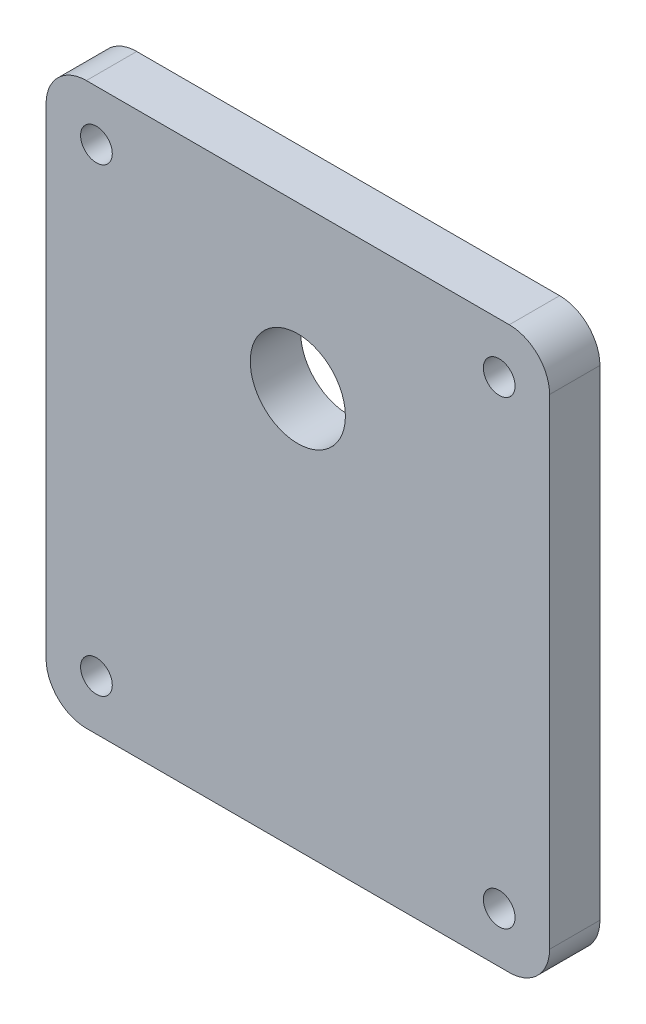
SolidWorks part; units mm, degrees
ref_plane "Front Plane" through (0, 0, 0) normal (0, 0, 1) x (1, 0, 0)
ref_plane "Top Plane" through (0, 0, 0) normal (0, 1, 0) x (1, 0, 0)
ref_plane "Right Plane" through (0, 0, 0) normal (1, 0, 0) x (0, 0, -1)
sketch "Sketch1" plane through (0, 0, 0) normal (0, 0, 1) x (1, 0, 0)
  line L0 (-19.6989, 23.2988) -> (-14.85, 29.7515)
  line L1 (-13.2512, 30.55) -> (13.2512, 30.55)
  line L2 (-20.1, 22.0973) -> (-20.1, -22.0973)
  line L3 (-13.2512, -30.55) -> (13.2512, -30.55)
  line L4 (20.1, 22.0973) -> (20.1, -22.0973)
  line L5 (-20.1, 30.55) -> (20.1, -30.55) construction
  line L6 (-20.1, -30.55) -> (20.1, 30.55) construction
  line L7 (14.85, 29.7515) -> (19.6989, 23.2988)
  line L8 (19.6989, -23.2988) -> (14.85, -29.7515)
  line L9 (-14.85, -29.7515) -> (-19.6989, -23.2988)
  arc A0 (-19.6989, -23.2988) -> (-20.1, -22.0973) centre (-18.1, -22.0973) cw
  arc A1 (-14.85, -29.7515) -> (-13.2512, -30.55) centre (-13.2512, -28.55) ccw
  arc A2 (14.85, -29.7515) -> (13.2512, -30.55) centre (13.2512, -28.55) cw
  arc A3 (19.6989, -23.2988) -> (20.1, -22.0973) centre (18.1, -22.0973) ccw
  arc A4 (19.6989, 23.2988) -> (20.1, 22.0973) centre (18.1, 22.0973) cw
  arc A5 (14.85, 29.7515) -> (13.2512, 30.55) centre (13.2512, 28.55) ccw
  arc A6 (-14.85, 29.7515) -> (-13.2512, 30.55) centre (-13.2512, 28.55) cw
  arc A7 (-19.6989, 23.2988) -> (-20.1, 22.0973) centre (-18.1, 22.0973) ccw
  point P0 (0, 0)
  point P16 (-20.1, -22.765)
  point P19 (-14.25, -30.55)
  point P22 (14.25, -30.55)
  point P25 (20.1, -22.765)
  point P28 (20.1, 22.765)
  point P31 (14.25, 30.55)
  point P34 (-14.25, 30.55)
  point P37 (-20.1, 22.765)
  dimension "D11" = 2
  dimension "D1" = 40.2
  dimension "D2" = 61.1
  dimension "D3" = 5.85
  dimension "D4" = 7.785
  dimension "D5" = 5.85
  dimension "D6" = 7.785
  dimension "D7" = 7.785
  dimension "D8" = 5.85
  dimension "D9" = 5.85
  dimension "D10" = 7.785
extrude "Boss-Extrude1" add sketch "Sketch1" against normal blind 6.35
sketch "Sketch2" plane through (0, 0, -6.35) normal (0, 0, -1) x (-1, 0, 0)
  line L0 (14.85, 29.7515) -> (14.85, -29.7515) construction
  line L1 (-14.85, 29.7515) -> (-14.85, -29.7515) construction
  line L2 (19.6989, 23.2988) -> (-19.6989, 23.2988) construction
  line L3 (20.1, -22.0973) -> (-20.1, -22.0973) construction
  line L4 (0, 30.55) -> (0, -30.55) construction
  line L5 (-13.2512, 30.55) -> (13.2512, 30.55) construction
  line L6 (13.2512, -30.55) -> (-13.2512, -30.55) construction
  circle A0 centre (17.3, 21.9488) radius 1.35
  circle A1 centre (17.3, -0.0512) radius 1.35
  circle A2 centre (17.3, -22.0512) radius 1.35
  circle A3 centre (11, -27.75) radius 1.385
  circle A4 centre (-11, -27.75) radius 1.385
  circle A5 centre (-17.3, -22.0512) radius 1.35
  circle A6 centre (-17.3, -0.0512) radius 1.35
  circle A7 centre (-17.3, 21.9488) radius 1.35
  dimension "D1" = 2.7
  dimension "D5" = 2.77
  dimension "D2" = 22
  dimension "D3" = 22
  dimension "D4" = 17.3
  dimension "D6" = 11
  dimension "D7" = 2.8
extrude "Cut-Extrude1" cut sketch "Sketch2" against normal through all
sketch "Sketch3" plane through (0, 0, -6.35) normal (0, 0, -1) x (-1, 0, 0)
  line L2 (-31.75, 38.2048) -> (31.75, 38.2048)
  line L3 (-31.75, 38.2048) -> (-31.75, -32.9152)
  line L4 (-31.75, -32.9152) -> (31.75, -32.9152)
  line L6 (31.75, 38.2048) -> (31.75, -32.9152)
  line L9 (-19.1605, 23.6188) -> (19.1605, 23.6188)
  line L10 (-19.1605, 23.6188) -> (-19.1605, -23.6188)
  line L11 (-19.1605, -23.6188) -> (19.1605, -23.6188)
  line L12 (19.1605, 23.6188) -> (19.1605, -23.6188)
  circle A0 centre (17.3, 21.9488) radius 1.35 construction
  point P0 (0, 0)
  point P6 (0, 0)
  dimension "D4" = 16.256
  dimension "D1" = 63.5
  dimension "D2" = 71.12
  dimension "D3" = 31.75
extrude "Boss-Extrude2" add sketch "Sketch3" against normal blind 6.35
sketch "Sketch5" plane through (0, 0, 0) normal (0, 0, 1) x (1, 0, 0)
  line L1 (-13.97, 30.9488) -> (13.97, 30.9488)
  line L2 (-13.97, 30.9488) -> (-13.97, -24.9312)
  line L3 (-13.97, -24.9312) -> (13.97, -24.9312)
  line L4 (13.97, 30.9488) -> (13.97, -24.9312)
  circle A0 centre (17.3, 21.9488) radius 1.35 construction
  dimension "D1" = 27.94
  dimension "D2" = 55.88
  dimension "D3" = 9
extrude "Cut-Extrude3" cut sketch "Sketch5" against normal through all
sketch "Sketch7" plane through (0, 0, 0) normal (0, 0, 1) x (1, 0, 0)
  line L1 (-31.75, -32.9152) -> (38.1, -32.9152)
  line L2 (-31.75, -32.9152) -> (-31.75, -32.5469)
  line L3 (-31.75, -32.5469) -> (38.1, -32.5469)
  line L4 (38.1, -32.9152) -> (38.1, -32.5469)
extrude "Cut-Extrude4" cut sketch "Sketch7" against normal blind 10
sketch "Sketch9" plane through (0, 0, 0) normal (0, 0, 1) x (1, 0, 0)
  line L0 (-31.75, 38.2048) -> (31.75, 38.2048) construction
  line L1 (31.75, 38.2048) -> (31.75, -32.5469) construction
  line L2 (31.75, -32.5469) -> (-31.75, -32.5469) construction
  circle A0 centre (25.4, 31.8548) radius 2
  circle A1 centre (-25.4, 31.8548) radius 2
  circle A2 centre (-25.4, -26.1969) radius 2
  circle A3 centre (25.4, -26.1969) radius 2
  dimension "D1" = 6.35
  dimension "D2" = 6.35
  dimension "D3" = 6.35
  dimension "D4" = 6.35
extrude "Cut-Extrude5" cut sketch "Sketch9" against normal through all
sketch "Sketch10" plane through (0, 0, -6.35) normal (0, 0, -1) x (-1, 0, 0)
  line L1 (-20.6612, 32.0396) -> (20.6612, 32.0396)
  line L2 (-20.6612, 32.0396) -> (-20.6612, -27.6285)
  line L3 (-20.6612, -27.6285) -> (20.6612, -27.6285)
  line L4 (20.6612, 32.0396) -> (20.6612, -27.6285)
extrude "Boss-Extrude3" add sketch "Sketch10" against normal blind 6.35
sketch "Sketch11" plane through (0, 0, 0) normal (0, 0, 1) x (1, 0, 0)
  line L0 (-31.75, 38.2048) -> (31.75, 38.2048) construction
  circle A0 centre (0, 17.8848) radius 6
  dimension "D1" = 20.32
extrude "Cut-Extrude6" cut sketch "Sketch11" against normal through all
fillet "Fillet1" radius 5.08 1 edges at (-31.75, 38.2048, -3.175)
fillet "Fillet2" radius 5.08 2 edges at (31.75, -32.5469, -3.175) (31.75, 38.2048, -3.175)
fillet "Fillet3" radius 5.08 1 edges at (-31.75, -32.5469, -3.175)
